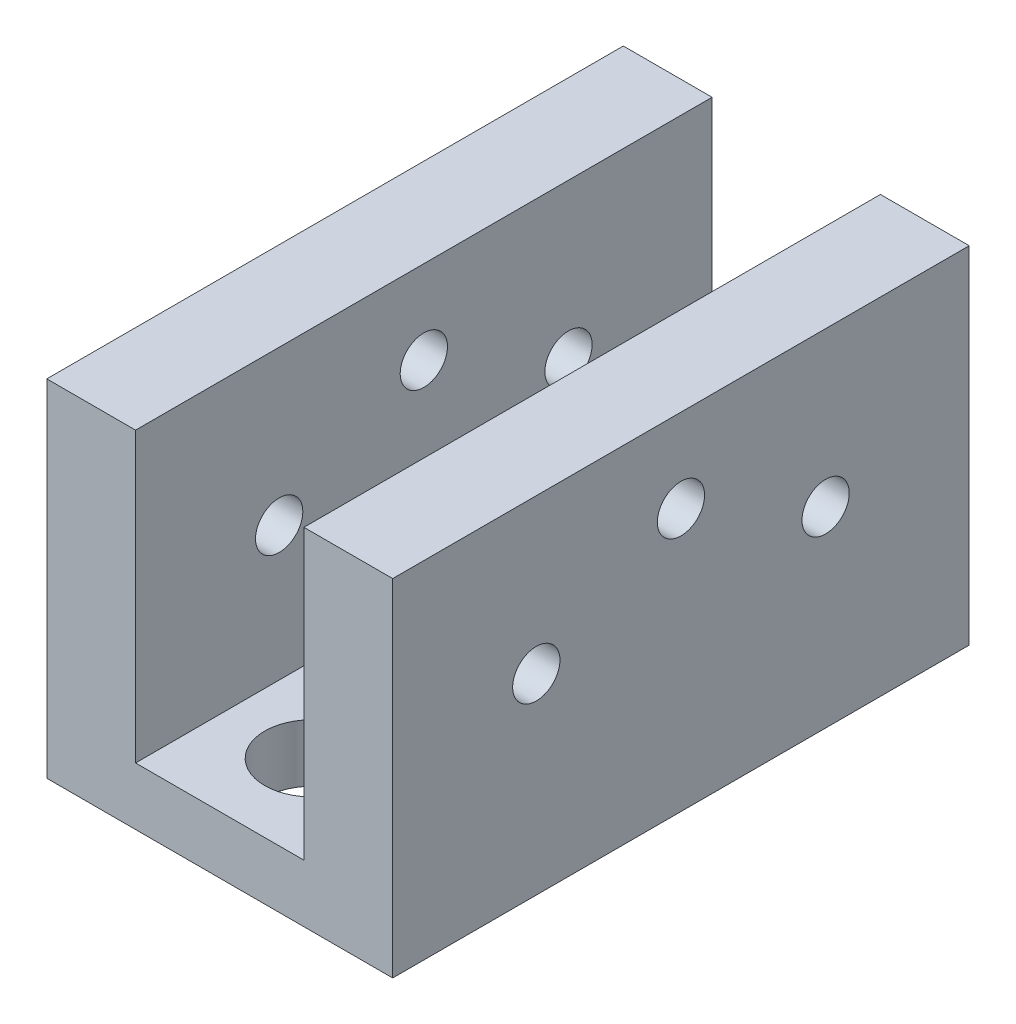
SolidWorks part; units mm, degrees
ref_plane "Front Plane" through (0, 0, 0) normal (0, 0, 1) x (1, 0, 0)
ref_plane "Top Plane" through (0, 0, 0) normal (0, 1, 0) x (1, 0, 0)
ref_plane "Right Plane" through (0, 0, 0) normal (1, 0, 0) x (0, 0, -1)
sketch "Sketch1" plane through (0, 0, 0) normal (0, 1, 0) x (1, 0, 0)
  line L0 (0, 25) -> (0, 17) construction
  line L1 (-15, -25) -> (15, -25)
  line L2 (-15, -25) -> (-15, 25)
  line L3 (-15, 25) -> (15, 25)
  line L4 (15, -25) -> (15, 25)
  line L5 (-15, -25) -> (15, 25) construction
  line L6 (-15, 25) -> (15, -25) construction
  line L7 (0, -17) -> (0, -25) construction
  circle A0 centre (0, 17) radius 4.1
  circle A1 centre (0, -17) radius 4.1
  point P0 (0, 0)
  dimension "D3" = 8.2
  dimension "D1" = 50
  dimension "D2" = 30
  dimension "D4" = 8
extrude "Boss-Extrude1" add sketch "Sketch1" along normal blind 5
sketch "Sketch2" plane through (0, 5, 0) normal (0, 1, 0) x (1, 0, 0)
  line L1 (-7.25, -9.75) -> (7.25, -9.75)
  line L3 (-7.25, 9.75) -> (7.25, 9.75)
  line L5 (15, 25) -> (15, -25)
  line L6 (15, -25) -> (15, 25) construction
  line L7 (0, 10) -> (0, 9.75) construction
  line L8 (15, 25) -> (-15, 25) construction
  line L11 (-15, 25) -> (-7.25, 25)
  line L12 (-7.25, 9.75) -> (-7.25, 25)
  line L13 (-15, -25) -> (15, -25) construction
  line L16 (15, 25) -> (7.25, 25)
  line L17 (7.25, 9.75) -> (7.25, 25)
  line L20 (15, -25) -> (7.25, -25)
  line L21 (7.25, -9.75) -> (7.25, -25)
  line L22 (0, -10) -> (0, -9.75) construction
  line L25 (-15, -25) -> (-7.25, -25)
  line L26 (-7.25, -9.75) -> (-7.25, -25)
  line L27 (-7, -17) -> (-7.25, -17) construction
  line L28 (7, -17) -> (7.25, -17) construction
  line L29 (-7, 17) -> (-7.25, 17) construction
  line L30 (7, 17) -> (7.25, 17) construction
  line L32 (-15, 25) -> (-15, -25)
  line L33 (-15, 25) -> (-15, -25) construction
  circle A0 centre (0, 17) radius 7 construction
  circle A1 centre (0, -17) radius 7 construction
  point P0 (0, 0)
  dimension "D1" = 14
  dimension "D2" = 0.25
extrude "Boss-Extrude2" add sketch "Sketch2" along normal blind 25
sketch "Sketch4" plane through (15, 0, 0) normal (1, 0, 0) x (0, 0, -1)
  line L1 (0, 0) -> (0, 10) construction
  line L2 (-25, 0) -> (25, 0) construction
  circle A3 centre (-12.5453, 16.63) radius 2.05
  circle A4 centre (12.5453, 16.63) radius 2.05
  circle A5 centre (0, 22.755) radius 2.05
  dimension "D6" = 4.1
  dimension "D5" = 10
  dimension "D1" = 12.5453
  dimension "D2" = 12.5453
  dimension "D3" = 6.125
  dimension "D4" = 6.125
  dimension "D7" = 6.63
extrude "Cut-Extrude1" cut sketch "Sketch4" against normal through all
sketch "Sketch5" plane through (0, 30, 0) normal (0, 1, 0) x (1, 0, 0)
  line L0 (15, 25) -> (7.25, 25) construction
  line L1 (-7.3, -25) -> (7.3, -25)
  line L2 (-7.3, -25) -> (-7.3, 25)
  line L3 (-7.3, 25) -> (7.3, 25)
  line L4 (7.3, -25) -> (7.3, 25)
  line L5 (-7.3, -25) -> (7.3, 25) construction
  line L6 (-7.3, 25) -> (7.3, -25) construction
  point P0 (0, 0)
  dimension "D1" = 14.6
extrude "Cut-Extrude2" cut sketch "Sketch5" against normal up to vertex (25 mm away)
